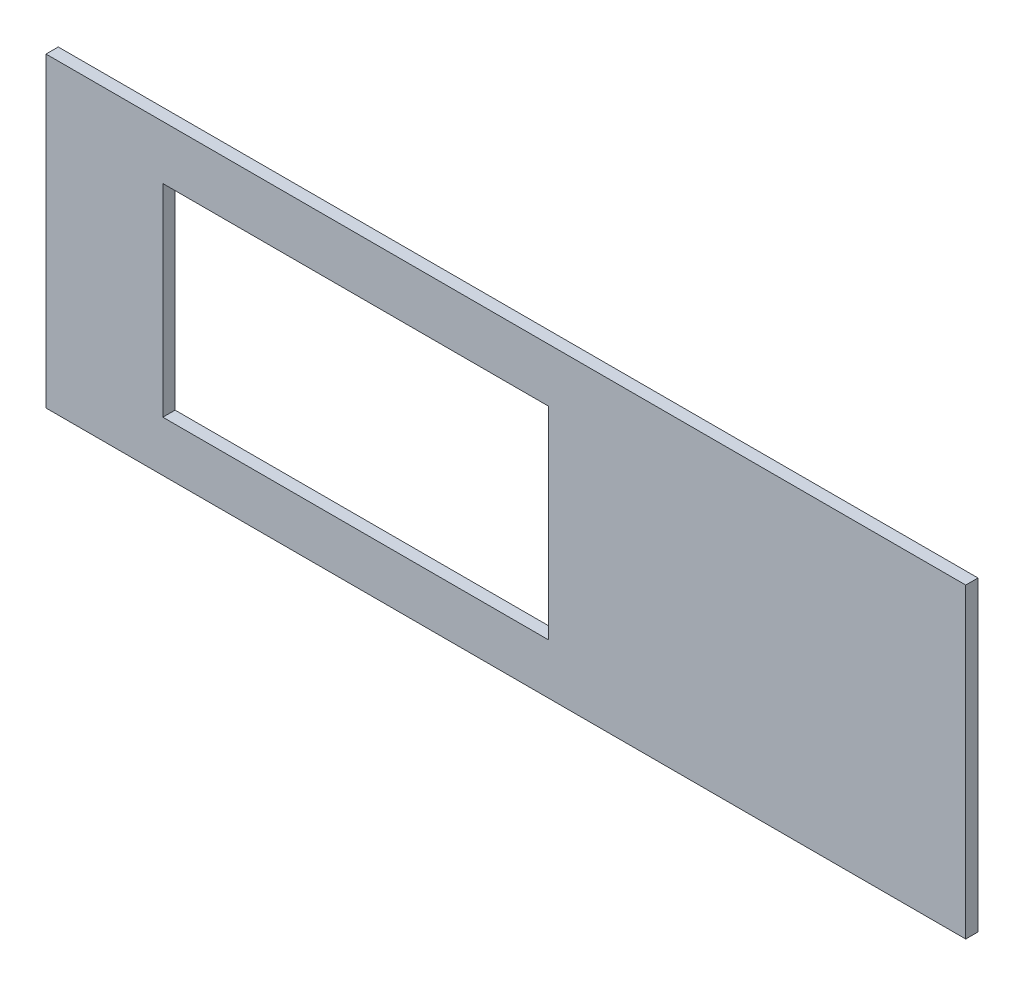
SolidWorks part; units mm, degrees
ref_plane "Front Plane" through (0, 0, 0) normal (0, 0, 1) x (1, 0, 0)
ref_plane "Top Plane" through (0, 0, 0) normal (0, 1, 0) x (1, 0, 0)
ref_plane "Right Plane" through (0, 0, 0) normal (1, 0, 0) x (0, 0, -1)
sketch "Sketch1" plane through (0, 0, 0) normal (0, 0, 1) x (1, 0, 0)
  line L1 (-352.6531, 0) -> (547.3469, 0)
  line L2 (-352.6531, 0) -> (-352.6531, 300)
  line L3 (-352.6531, 300) -> (547.3469, 300)
  line L4 (547.3469, 0) -> (547.3469, 300)
  line L5 (139.1501, 49.4032) -> (-238.3169, 49.4032)
  line L6 (139.1501, 49.4032) -> (139.1501, 247.444)
  line L7 (139.1501, 247.444) -> (-238.3169, 247.444)
  line L8 (-238.3169, 49.4032) -> (-238.3169, 247.444)
extrude "Boss-Extrude2" add sketch "Sketch1" against normal blind 12
